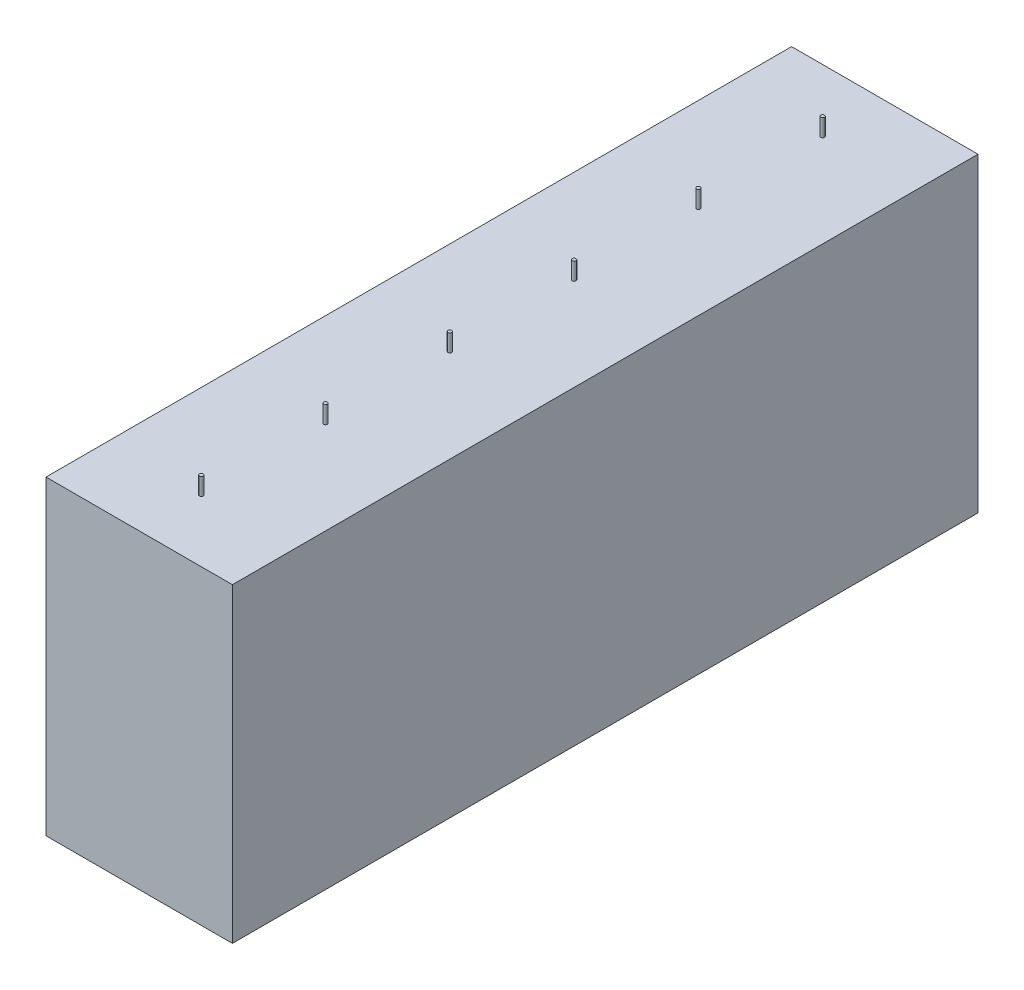
SolidWorks part; units mm, degrees
ref_plane "Front Plane" through (0, 0, 0) normal (0, 0, 1) x (1, 0, 0)
ref_plane "Top Plane" through (0, 0, 0) normal (0, 1, 0) x (1, 0, 0)
ref_plane "Right Plane" through (0, 0, 0) normal (1, 0, 0) x (0, 0, -1)
sketch "Sketch1" plane through (0, 0, 0) normal (0, 0, 1) x (1, 0, 0)
  line L1 (-83.0986, 178.169) -> (216.9014, 178.169)
  line L2 (-83.0986, 178.169) -> (-83.0986, -321.831)
  line L3 (-83.0986, -321.831) -> (216.9014, -321.831)
  line L4 (216.9014, 178.169) -> (216.9014, -321.831)
  dimension "D1" = 300
  dimension "D2" = 500
extrude "Boss-Extrude1" add sketch "Sketch1" along normal blind 1200
sketch "Sketch2" plane through (0, 178.169, 0) normal (0, 1, 0) x (1, 0, 0)
  line L1 (216.9014, 0) -> (-83.0986, 0) construction
  circle A1 centre (66.9014, -100) radius 3
  circle A2 centre (66.9014, -300) radius 3
  circle A3 centre (66.9014, -500) radius 3
  circle A4 centre (66.9014, -700) radius 3
  circle A5 centre (66.9014, -900) radius 3
  circle A6 centre (66.9014, -1100) radius 3
  dimension "D1" = 100
  dimension "D2" = 6
extrude "Boss-Extrude2" add sketch "Sketch2" along normal blind 28
